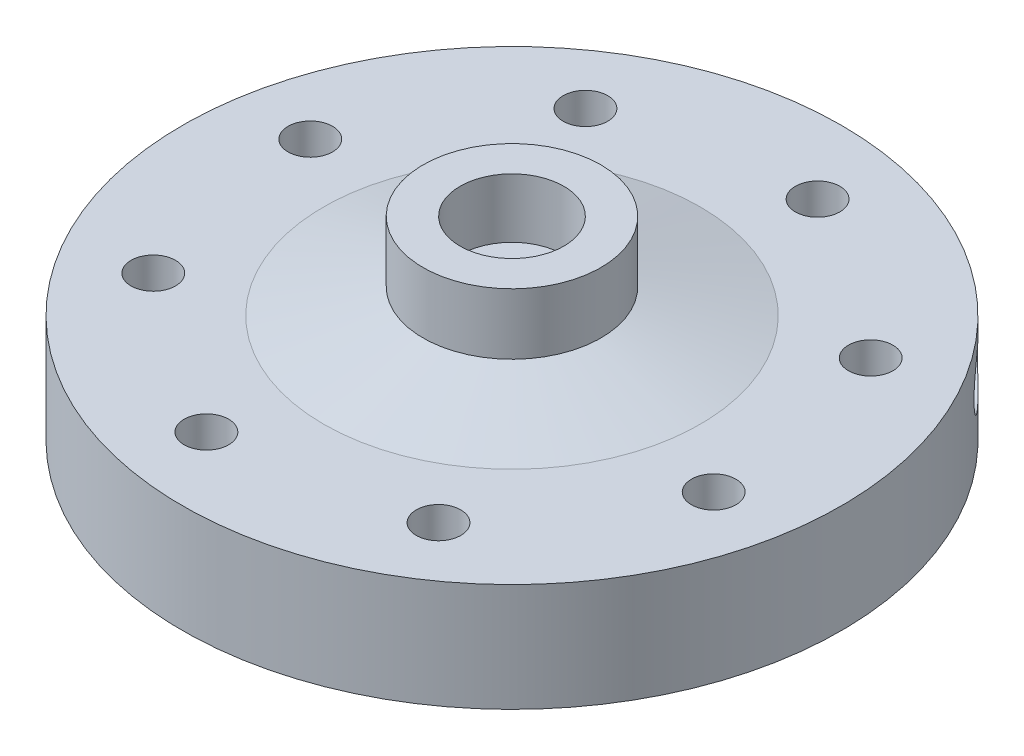
SolidWorks part; units mm, degrees
material "1060 Alloy"
ref_plane "Front" through (0, 0, 0) normal (0, 0, 1) x (1, 0, 0)
ref_plane "Top" through (0, 0, 0) normal (0, 1, 0) x (1, 0, 0)
ref_plane "Right" through (0, 0, 0) normal (1, 0, 0) x (0, 0, -1)
sketch "Sketch1" plane through (0, 0, 0) normal (0, 1, 0) x (1, 0, 0)
  circle A4 centre (0, 0) radius 44.45
  point P0 (0, 0)
  point P17 (0, 0)
  dimension "D1" = 88.9
extrude "body extrusion" add sketch "Sketch1" along normal blind 21.1893
sketch "Sketch2" plane through (0, 0, 0) normal (0, 0, 1) x (1, 0, 0)
  line L0 (0, 0) -> (0, 9.1893)
  line L1 (0, 9.1893) -> (3.81, 9.1893)
  line L2 (3.81, 9.1893) -> (22.09, 4.5875)
  line L3 (22.09, 4.5875) -> (22.09, 0)
  line L4 (22.09, 0) -> (0, 0)
  line L5 (-44.45, 0) -> (44.45, 0) construction
  dimension "D1" = 22.09
  dimension "D3" = 4.5875
  dimension "D2" = 3.81
  dimension "D4" = 9.1893
revolve "main chamber" cut sketch "Sketch2" angle 360 about L0
sketch "Sketch6" plane through (0, 21.1893, 0) normal (0, 1, 0) x (1, 0, 0)
  circle A0 centre (0, 0) radius 3.81
  dimension "D1" = 7.62
extrude "De" cut sketch "Sketch6" against normal blind 100
sketch "Sketch7" plane through (0, 21.1893, 0) normal (0, 1, 0) x (1, 0, 0)
  circle A0 centre (0, 0) radius 7
  dimension "D1" = 14
extrude "inlet tap" cut sketch "Sketch7" against normal blind 8
sketch "outlet plane ref 1" plane through (0, 0, 0) normal (0, -1, 0) x (1, 0, 0)
  line L0 (0, 0) -> (0, -22.09) construction
  line L1 (0, -22.09) -> (29.8354, -32.9492) construction
  line L2 (2.057, -21.994) -> (32.6287, -30.1857) construction
  line L3 (2.057, -21.994) -> (0, -21.4428) construction
  circle A0 centre (0, 0) radius 22.09 construction
  circle A1 centre (0, 0) radius 44.45 construction
  dimension "D1" = 110
  dimension "D2" = 0.7937
  dimension "D3" = 5
sketch "outlet plane ref 2" plane through (0, 21.1893, 0) normal (0, 1, 0) x (1, 0, 0)
  line L0 (0, 21.4428) -> (32.6287, 30.1857) construction
ref_plane "outlet axial plane" through (-5.3607, 0, -20.0064) normal (0.2588, 0, 0.9659) x (0.9659, 0, -0.2588)
sketch "Sketch11" plane through (-5.3607, 0, -20.0064) normal (0.2588, 0, 0.9659) x (0.9659, 0, -0.2588)
  line L0 (5.5498, 21.1893) -> (5.5498, 0) construction
  line L1 (5.5498, 3.7938) -> (105.5498, 3.7938) construction
  line L2 (5.5498, 4.4012) -> (105.1693, 13.1168)
  line L4 (5.5498, 4.4012) -> (5.5498, 3.7938)
  line L5 (5.5498, 3.7938) -> (105.1693, 3.7938)
  line L6 (105.1693, 3.7938) -> (105.1693, 13.1168)
  line L7 (7.6794, 0) -> (7.6794, 4.5875) construction
  line L8 (7.6794, 0) -> (5.5498, 0) construction
  line L10 (5.7173, 0) -> (37.3467, 0) construction
  line L11 (22.09, 4.5875) -> (-22.09, 4.5875) construction
  dimension "D3" = 5
  dimension "D2" = 100
  dimension "D4" = 100
  dimension "D1" = 0.7937
revolve "conical outlet" cut sketch "Sketch11" angle 360 about L5
sketch "Sketch16" plane through (0, 0, 0) normal (0, 0, 1) x (1, 0, 0)
  line L0 (12, 21.1893) -> (12, 12.9562)
  line L1 (44.45, 21.1893) -> (-44.45, 21.1893) construction
  line L2 (12, 12.9562) -> (25.4, 9.5829)
  line L3 (25.4, 9.5829) -> (44.45, 9.5829)
  line L4 (44.45, 0) -> (44.45, 21.1893) construction
  line L5 (7, 13.1893) -> (7, 21.1893) construction
  line L7 (22.09, 4.5875) -> (3.81, 9.1893) construction
  line L8 (0, 0) -> (0, 21.1893) construction
  line L9 (34.925, 21.1893) -> (34.925, 0) construction
  line L11 (31.925, 21.1893) -> (31.925, 0) construction
  line L13 (12, 21.1893) -> (44.45, 21.1893)
  line L14 (44.45, 21.1893) -> (44.45, 9.5829)
  line L15 (-44.45, 0) -> (44.45, 0) construction
  dimension "D1" = 5
  dimension "D3" = 34.925
  dimension "D4" = 3
  dimension "D5" = 6.525
  dimension "D2" = 5
revolve "outer profile" cut sketch "Sketch16" angle 360 about L8
sketch "exit plane ref 1" plane through (0, 9.5829, 0) normal (0, 1, 0) x (1, 0, 0)
  line L0 (6.6608, 24.5111) -> (29.838, 32.9469) construction
  line L1 (29.838, 32.9469) -> (0.0088, 22.09) construction
  line L2 (29.838, 32.9469) -> (0.0088, 22.09) construction
  line L3 (11.1912, 22.8017) -> (35.2733, 27.048) construction
  line L4 (4.5129, 21.6241) -> (35.2733, 27.048) construction
  line L5 (4.5129, 21.6241) -> (35.2733, 27.048) construction
  line L6 (8.8409, 23.8117) -> (32.6287, 30.1857)
  line L7 (30.7152, 29.6729) -> (31.5925, 26.399)
  line L8 (30.7152, 29.6729) -> (29.838, 32.9469)
  circle A0 centre (0, 0) radius 44.45 construction
  circle A1 centre (0, 0) radius 25.4 construction
  dimension "D1" = 5
sketch "exit plane ref 2" plane through (0, 0, 0) normal (0, -1, 0) x (1, 0, 0)
  line L0 (31.5925, -26.399) -> (29.838, -32.9469)
sketch "Sketch26" plane through (0, 0, 0) normal (0, -1, 0) x (1, 0, 0)
  circle A0 centre (0, 0) radius 44.45
  circle A1 centre (0, 0) radius 22.09
  dimension "D1" = 44.18
extrude "base riser" add sketch "Sketch26" along normal blind 5
ref_plane "outlet plane" through (36.0759, 0, -9.6665) normal (0.9659, 0, -0.2588) x (-0.2588, 0, -0.9659)
sketch "Sketch13" plane through (0, 21.1893, 0) normal (0, 1, 0) x (1, 0, 0)
  line L2 (29.838, 32.9469) -> (0.0088, 22.09) construction
  circle A0 centre (0, 0) radius 34.925 construction
  circle A1 centre (7.0073, 34.2148) radius 3
  dimension "D1" = 69.85
  dimension "D2" = 6
  dimension "D3" = 9
extrude "bolt holes" cut sketch "Sketch13" against normal blind 100
pattern_circular "bolt pattern" count 8 over 360 about axis through (0, 0, 0) along (0, 1, 0) of "bolt holes"
equation "\"de\"= .3in"
equation "\"D1@Sketch1\"=\"impeller housing diameter\""
equation "\"D1@body extrusion\" = \"impeller housing thickness\""
equation "\"D2@Sketch2\"=\"de\"/2"
equation "\"D3@Sketch2\"=\"impeller cavity outer height\""
equation "\"D1@Sketch2\"=\"impeller cavity diameter\"/2"
equation "\"D1@Sketch6\"=\"de\""
equation "\"D1@De\" = 100mm"
equation "\"D1@Sketch7\"=\"impeller housing threaded inlet diameter\""
equation "\"D1@inlet tap\" = \"impeller housing threaded inlet depth\""
equation "\"D4@Sketch2\"=\"impeller cavity center height\""
equation "\"z\"= 6"
equation "\"d2\"= 1.7in"
equation "\"d_exit\"=\"b2\""
equation "\"theta\"= 15"
equation "\"b2\"= .0625in"
equation "\"b1\"= \"b2\" + (\"d2\"/2 - \"de\"/2)*sin(\"theta\")"
equation "\"s\"= ( 1/\"z\")*(3.14*\"de\" - (3.14*(\"de\"^2) / (4*(\"b1\"))))"
equation "\"s_opening\"= (3.14*\"de\" - \"z\"*\"s\")/\"z\""
equation "\"area_eye\"=3.14*(\"de\"^2)/4"
equation "\"single_channel_area\"=\"s_opening\"*\"b1\""
equation "\"impeller upper clearance\"= .5mm"
equation "\"impeller horizontal clearance\"= .5mm"
equation "\"impeller bottom clearance\"= .5mm"
equation "\"impeller base thickness\"= 2mm"
equation "\"impeller boss depth\"= 14mm"
equation "\"impeller cavity center height\"= \"impeller bottom clearance\" + \"impeller base thickness\" + \"b1\" + \"impeller upper clearance\""
equation "\"impeller cavity diameter\"= 2 * \"impeller horizontal clearance\" + \"d2\""
equation "\"impeller cavity outer height\"= \"impeller bottom clearance\" + \"impeller upper clearance\" + \"impeller base thickness\" + \"b2\""
equation "\"impeller housing bolt count\"= 8"
equation "\"impeller housing bolt diameter\"= 6mm"
equation "\"impeller housing bolt pattern diameter\"= 2.75in"
equation "\"impeller housing o-ring channel height\"= 1.5mm"
equation "\"impeller housing o ring channel width\"= 1.5mm"
equation "\"impeller housing o-ring diameter\"= 2in"
equation "\"impeller housing threaded inlet diameter\"= 14mm"
equation "\"impeller housing threaded inlet depth\"= 8mm"
equation "\"impeller housing thickness\"= \"impeller housing threaded inlet depth\" + \"impeller cavity center height\"+4mm"
equation "\"impeller housing exit threaded diameter\"= 8mm"
equation "\"impeller housing exit threaded depth\"= 8mm"
equation "\"impeller housing diameter\"= 3.5in"
equation "\"impeller housing diffuser conical angle\"=10"
equation "\"impeller housing diffuser tangent angle\"=20"
equation "\"motor to housing distance\"= 60mm"
equation "\"D1@outlet plane ref 1\" = \"impeller housing diffuser tangent angle\" + 90"
equation "\"D2@outlet plane ref 1\" = \"d_exit\" / 2"
equation "\"D3@outlet plane ref 1\" = \"impeller housing diffuser conical angle\" / 2"
equation "\"D1@Sketch11\"=\"d_exit\"/2"
equation "\"D3@Sketch11\"=\"impeller housing diffuser conical angle\"/2"
equation "\"D1@Sketch13\"=\"impeller housing bolt pattern diameter\""
equation "\"D2@Sketch13\"=\"impeller housing bolt diameter\""
equation "\"D3@Sketch13\"=\"impeller housing bolt diameter\"/2+6mm"
equation "\"D3@Sketch16\"=\"impeller housing bolt pattern diameter\"/2"
equation "\"D4@Sketch16\"=\"impeller housing bolt diameter\"/2"
equation "\"D5@Sketch16\"=\"impeller housing diameter\"/2 - \"impeller housing bolt pattern diameter\"/2 - \"impeller housing bolt diameter\"/2"
equation "\"D1@exit plane ref 1\" = \"impeller housing diffuser conical angle\" / 2"
equation "\"D1@bolt pattern\" = \"impeller housing bolt count\""
equation "\"impeller housing outlet purchase\"= 5mm"
equation "\"D1@base riser\"=\"impeller housing outlet purchase\""
equation "\"D1@Sketch26\"=\"impeller cavity diameter\""
